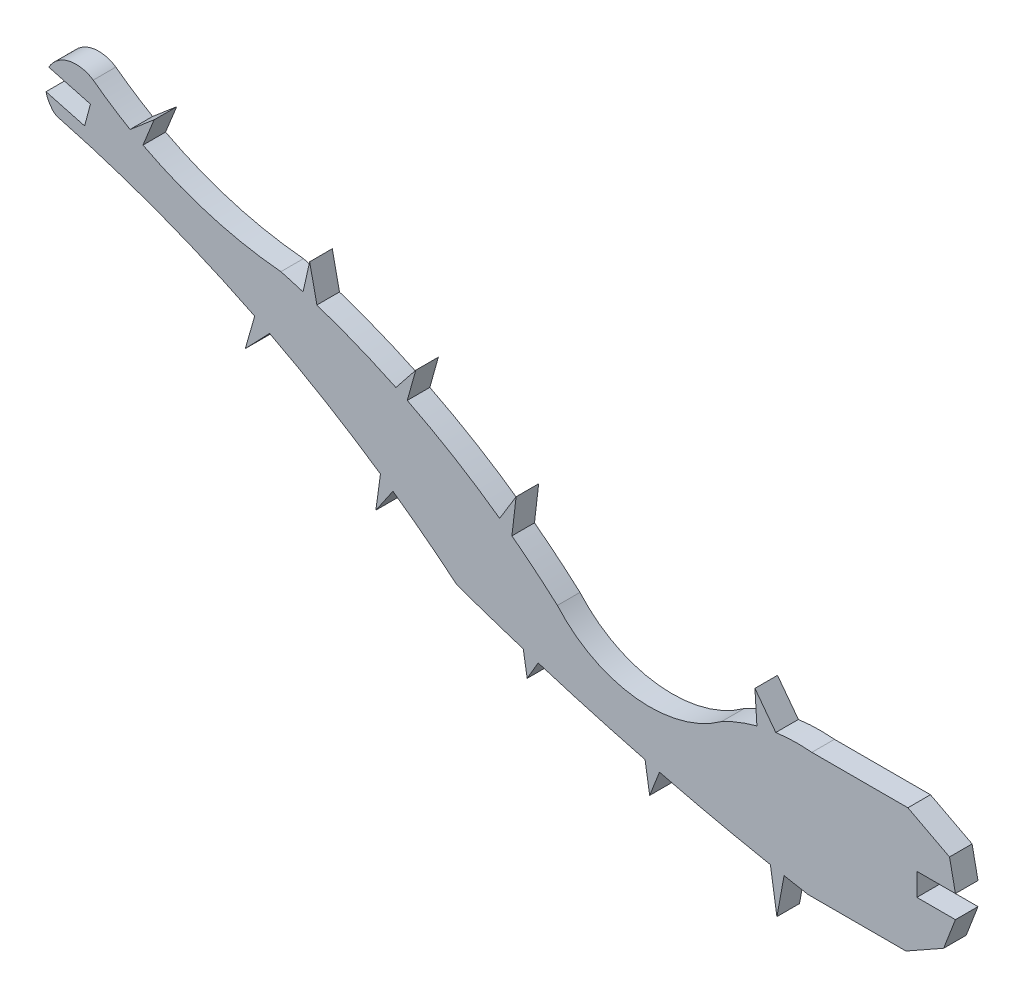
SolidWorks part; units mm, degrees
ref_plane "Front Plane" through (0, 0, 0) normal (0, 0, 1) x (1, 0, 0)
ref_plane "Top Plane" through (0, 0, 0) normal (0, 1, 0) x (1, 0, 0)
ref_plane "Right Plane" through (0, 0, 0) normal (1, 0, 0) x (0, 0, -1)
sketch "Sketch1" plane through (0, 0, 0) normal (0, 0, 1) x (1, 0, 0)
  line L0 (-65.6284, -1.524) -> (-63.0257, -1.524)
  line L1 (-63.0257, -1.524) -> (-63.8225, -3.598)
  line L2 (-63.8225, -3.598) -> (-66.3647, -5.0287)
  line L3 (-66.3647, -5.0287) -> (-72.9704, -5.0287)
  line L4 (-65.6284, -1.524) -> (-65.6284, 0)
  line L5 (-65.6284, 0) -> (-63.0257, 0)
  line L6 (-63.0257, 0) -> (-63.4241, 1.9415)
  line L7 (-63.4241, 1.9415) -> (-66.2339, 3.411)
  line L8 (-66.2339, 3.411) -> (-72.7138, 3.411)
  line L9 (-75.515, -4.5539) -> (-75.0731, -7.373)
  line L10 (-75.0731, -7.373) -> (-74.5897, -4.7319)
  line L11 (-82.9989, -2.8901) -> (-83.6622, -4.5806)
  line L12 (-83.6622, -4.5806) -> (-83.9742, -2.6434)
  line L13 (-91.1892, -0.5983) -> (-91.9292, -1.8731)
  line L14 (-91.9292, -1.8731) -> (-92.1925, -0.2826)
  line L15 (-100.9893, 4.5357) -> (-102.1415, 2.8517)
  line L16 (-102.1415, 2.8517) -> (-101.8308, 5.1219)
  line L18 (-109.3161, 9.5976) -> (-110.9523, 7.8915)
  line L19 (-110.9523, 7.8915) -> (-110.3196, 10.1056)
  line L20 (-118.7309, 16.8114) -> (-117.1106, 18.1844)
  line L21 (-117.1106, 18.1844) -> (-117.8595, 16.3312)
  line L22 (-107.057, 13.1529) -> (-106.6093, 15.1377)
  line L23 (-106.6093, 15.1377) -> (-106.1226, 12.8531)
  line L24 (-100.7871, 10.6983) -> (-99.4487, 12.3811)
  line L25 (-99.4487, 12.3811) -> (-100.0237, 10.3241)
  line L26 (-93.7884, 6.5503) -> (-92.677, 8.369)
  line L27 (-92.677, 8.369) -> (-92.9595, 5.9398)
  line L28 (-75.1493, 3.3533) -> (-76.5584, 5.229)
  line L29 (-76.5584, 5.229) -> (-76.4241, 3.0995)
  arc A0 (-72.9704, -5.0287) -> (-74.5897, -4.7319) centre (-46.8163, 142.1944) cw
  arc A1 (-72.7138, 3.411) -> (-75.1493, 3.3533) centre (-73.6769, -7.373) ccw
  arc A2 (-78.8093, 2.1601) -> (-89.8908, 3.411) centre (-83.6622, 8.8789) cw
  arc A3 (-89.8908, 3.411) -> (-92.9595, 5.9398) centre (-120.6397, -30.7762) ccw
  arc A4 (-108.5527, 13.5878) -> (-117.8595, 16.3312) centre (-106.33, 38.286) cw
  arc A5 (-96.6721, 1.2225) -> (-100.9893, 4.5357) centre (-141.4842, -52.6986) ccw
  arc A6 (-121.2164, 18.4533) -> (-123.9597, 15.3314) centre (-122.3739, 16.7042) ccw
  arc A7 (-76.4241, 3.0995) -> (-78.8093, 2.1601) centre (-73.6769, -7.373) ccw
  arc A8 (-75.515, -4.5539) -> (-82.9989, -2.8901) centre (-46.8163, 142.1944) cw
  arc A9 (-83.9742, -2.6434) -> (-91.1892, -0.5983) centre (-46.8163, 142.1944) cw
  arc A10 (-92.1925, -0.2826) -> (-96.6721, 1.2225) centre (-46.8163, 142.1944) cw
  arc A11 (-93.7884, 6.5503) -> (-100.0237, 10.3241) centre (-120.6397, -30.7762) ccw
  arc A12 (-100.7871, 10.6983) -> (-106.1226, 12.8531) centre (-120.6397, -30.7762) ccw
  arc A13 (-101.8308, 5.1219) -> (-109.3161, 9.5976) centre (-141.4842, -52.6986) ccw
  arc A14 (-110.3196, 10.1056) -> (-123.5625, 15.0835) centre (-141.4842, -52.6986) ccw
  arc A15 (-107.057, 13.1529) -> (-108.5527, 13.5878) centre (-120.6397, -30.7762) ccw
  arc A16 (-118.7309, 16.8114) -> (-121.2164, 18.4533) centre (-106.33, 38.286) cw
  arc A17 (-123.5625, 15.0835) -> (-123.9597, 15.3314) centre (-123.3596, 15.8509) cw
  dimension "D1" = 0.7937
extrude "Boss-Extrude1" add sketch "Sketch1" along normal blind 1.524
sketch "Sketch2" plane through (0, 0, 1.524) normal (0, 0, 1) x (1, 0, 0)
  line L0 (-126.0705, 17.416) -> (-121.6024, 16.2187) construction
  line L1 (-126.2677, 16.6799) -> (-121.7997, 15.4827)
  line L2 (-125.8733, 18.152) -> (-121.4052, 16.9548)
  line L3 (-126.2677, 16.6799) -> (-125.8733, 18.152)
  line L4 (-121.7997, 15.4827) -> (-121.4052, 16.9548)
extrude "Cut-Extrude1" cut sketch "Sketch2" against normal blind 1.524
